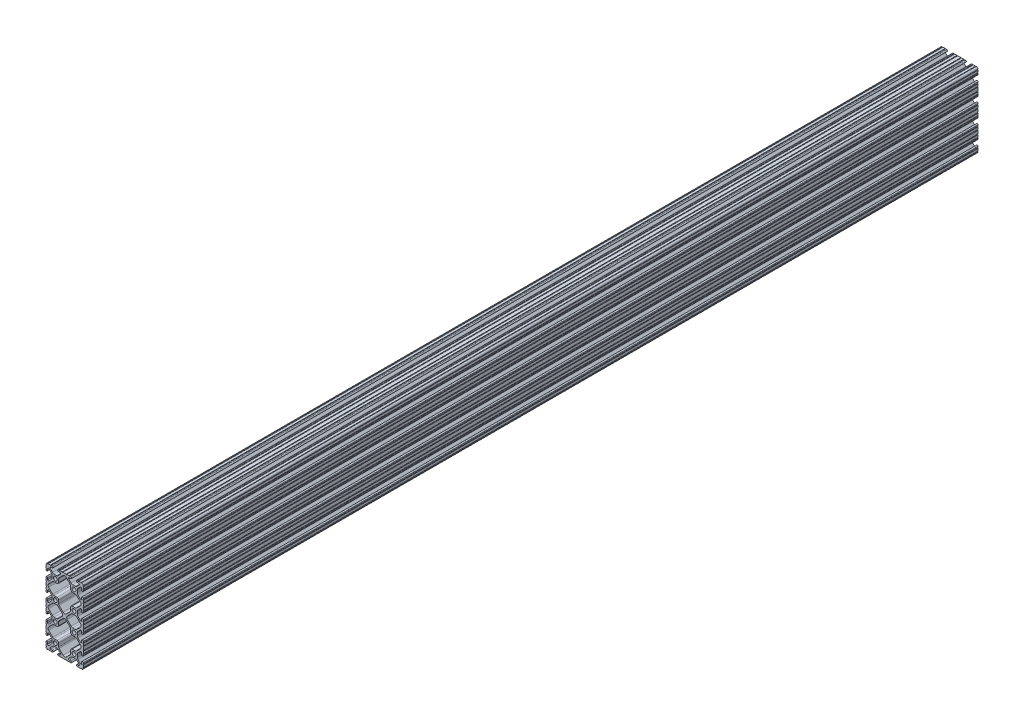
SolidWorks part; units mm, degrees
ref_plane "Front Plane" through (0, 0, 0) normal (0, 0, 1) x (1, 0, 0)
ref_plane "Top Plane" through (0, 0, 0) normal (0, 1, 0) x (1, 0, 0)
ref_plane "Right Plane" through (0, 0, 0) normal (1, 0, 0) x (0, 0, -1)
sketch "Sketch1" plane through (0, 0, 0) normal (0, 0, 1) x (1, 0, 0)
  line L0 (2.286, 55.2958) -> (-2.0184, 55.2958)
  line L1 (-3.5809, 55.943) -> (-9.0725, 61.4345)
  line L2 (-9.0725, 65.5655) -> (-3.5809, 71.057)
  line L3 (-2.0184, 71.7042) -> (2.286, 71.7042)
  line L4 (4.4958, 73.914) -> (4.4958, 78.2184)
  line L5 (5.143, 79.7809) -> (10.6345, 85.2725)
  line L6 (14.7655, 85.2725) -> (20.257, 79.7809)
  line L7 (20.9042, 78.2184) -> (20.9042, 73.914)
  line L8 (23.114, 71.7042) -> (27.4184, 71.7042)
  line L9 (28.9809, 71.057) -> (34.4725, 65.5655)
  line L10 (34.4725, 61.4345) -> (28.9809, 55.943)
  line L11 (27.4184, 55.2958) -> (23.114, 55.2958)
  line L12 (20.9042, 53.086) -> (20.9042, 48.7816)
  line L13 (20.257, 47.2191) -> (14.7655, 41.7275)
  line L14 (10.6345, 41.7275) -> (5.143, 47.2191)
  line L15 (4.4958, 48.7816) -> (4.4958, 53.086)
  line L16 (4.4958, 23.114) -> (4.4958, 27.4184)
  line L17 (5.143, 28.9809) -> (10.6345, 34.4725)
  line L18 (14.7655, 34.4725) -> (20.257, 28.9809)
  line L19 (20.9042, 27.4184) -> (20.9042, 23.114)
  line L20 (23.114, 20.9042) -> (27.4184, 20.9042)
  line L21 (28.9809, 20.257) -> (34.4725, 14.7655)
  line L22 (34.4725, 10.6345) -> (28.9809, 5.143)
  line L23 (27.4184, 4.4958) -> (23.114, 4.4958)
  line L24 (20.9042, 2.286) -> (20.9042, -2.0184)
  line L25 (20.257, -3.5809) -> (14.7655, -9.0725)
  line L26 (10.6345, -9.0725) -> (5.143, -3.5809)
  line L27 (4.4958, -2.0184) -> (4.4958, 2.286)
  line L28 (2.286, 4.4958) -> (-2.0184, 4.4958)
  line L29 (-3.5809, 5.143) -> (-9.0725, 10.6345)
  line L30 (-9.0725, 14.7655) -> (-3.5809, 20.257)
  line L31 (-2.0184, 20.9042) -> (2.286, 20.9042)
  line L32 (27.0186, 29.8958) -> (23.7824, 29.8958)
  line L33 (21.5373, 30.8258) -> (16.3286, 36.0346)
  line L34 (16.3286, 40.1654) -> (21.5373, 45.3742)
  line L35 (23.7824, 46.3042) -> (27.0186, 46.3042)
  line L36 (29.2636, 45.3743) -> (34.4725, 40.1655)
  line L37 (34.4725, 36.0345) -> (29.2636, 30.8257)
  line L38 (1.6176, 29.8958) -> (-1.6186, 29.8958)
  line L39 (-3.8636, 30.8257) -> (-9.0725, 36.0345)
  line L40 (-9.0725, 40.1655) -> (-3.8636, 45.3743)
  line L41 (-1.6186, 46.3042) -> (1.6176, 46.3042)
  line L42 (3.8627, 45.3742) -> (9.0714, 40.1654)
  line L43 (9.0714, 36.0346) -> (3.8627, 30.8258)
  line L44 (-12.7, 40.2336) -> (-12.7, 35.9664)
  line L45 (-12.7, 34.9504) -> (-12.7, 32.004)
  line L46 (-12.7, 30.988) -> (-12.7, 29.7434)
  line L47 (-10.4902, 29.7434) -> (-10.4902, 31.8743)
  line L48 (-8.7558, 32.5927) -> (-5.4258, 29.2627)
  line L49 (-4.4958, 27.0176) -> (-4.4958, 23.7824)
  line L50 (-5.4258, 21.5373) -> (-8.7558, 18.2073)
  line L51 (-10.4902, 18.9257) -> (-10.4902, 21.0566)
  line L52 (-12.7, 21.0566) -> (-12.7, 19.812)
  line L53 (-12.7, 18.796) -> (-12.7, 15.8496)
  line L54 (-12.7, 14.8336) -> (-12.7, 10.5664)
  line L55 (-12.7, 9.5504) -> (-12.7, 6.604)
  line L56 (-12.7, 5.588) -> (-12.7, 4.3434)
  line L57 (-10.4902, 4.3434) -> (-10.4902, 6.4743)
  line L58 (-8.7558, 7.1927) -> (-5.4258, 3.8627)
  line L59 (-4.4958, 1.6176) -> (-4.4958, -1.6176)
  line L60 (-5.4258, -3.8627) -> (-8.7558, -7.1927)
  line L61 (-10.4902, -6.4743) -> (-10.4902, -4.3434)
  line L62 (-12.7, -4.3434) -> (-12.7, -5.588)
  line L63 (-12.7, -6.604) -> (-12.7, -9.5504)
  line L64 (-9.5504, -12.7) -> (-6.604, -12.7)
  line L65 (-5.588, -12.7) -> (-4.3434, -12.7)
  line L66 (-4.3434, -10.4902) -> (-6.4743, -10.4902)
  line L67 (-7.1927, -8.7558) -> (-3.8627, -5.4258)
  line L68 (-1.6176, -4.4958) -> (1.6176, -4.4958)
  line L69 (3.8627, -5.4258) -> (7.1927, -8.7558)
  line L70 (6.4743, -10.4902) -> (4.3434, -10.4902)
  line L71 (4.3434, -12.7) -> (5.588, -12.7)
  line L72 (6.604, -12.7) -> (9.5504, -12.7)
  line L73 (10.5664, -12.7) -> (14.8336, -12.7)
  line L74 (15.8496, -12.7) -> (18.796, -12.7)
  line L75 (19.812, -12.7) -> (21.0566, -12.7)
  line L76 (21.0566, -10.4902) -> (18.9257, -10.4902)
  line L77 (18.2073, -8.7558) -> (21.5373, -5.4258)
  line L78 (23.7824, -4.4958) -> (27.0176, -4.4958)
  line L79 (29.2627, -5.4258) -> (32.5927, -8.7558)
  line L80 (31.8743, -10.4902) -> (29.7434, -10.4902)
  line L81 (29.7434, -12.7) -> (30.988, -12.7)
  line L82 (32.004, -12.7) -> (34.9504, -12.7)
  line L83 (38.1, -9.5504) -> (38.1, -6.604)
  line L84 (38.1, -5.588) -> (38.1, -4.3434)
  line L85 (35.8902, -4.3434) -> (35.8902, -6.4743)
  line L86 (34.1558, -7.1927) -> (30.8258, -3.8627)
  line L87 (29.8958, -1.6176) -> (29.8958, 1.6176)
  line L88 (30.8258, 3.8627) -> (34.1558, 7.1927)
  line L89 (35.8902, 6.4743) -> (35.8902, 4.3434)
  line L90 (38.1, 4.3434) -> (38.1, 5.588)
  line L91 (38.1, 6.604) -> (38.1, 9.5504)
  line L92 (38.1, 10.5664) -> (38.1, 14.8336)
  line L93 (38.1, 15.8496) -> (38.1, 18.796)
  line L94 (38.1, 19.812) -> (38.1, 21.0566)
  line L95 (35.8902, 21.0566) -> (35.8902, 18.9257)
  line L96 (34.1558, 18.2073) -> (30.8258, 21.5373)
  line L97 (29.8958, 23.7824) -> (29.8958, 27.0176)
  line L98 (30.8258, 29.2627) -> (34.1558, 32.5927)
  line L99 (35.8902, 31.8743) -> (35.8902, 29.7434)
  line L100 (38.1, 29.7434) -> (38.1, 30.988)
  line L101 (38.1, 32.004) -> (38.1, 34.9504)
  line L102 (38.1, 35.9664) -> (38.1, 40.2336)
  line L103 (38.1, 41.2496) -> (38.1, 44.196)
  line L104 (38.1, 45.212) -> (38.1, 46.4566)
  line L105 (35.8902, 46.4566) -> (35.8902, 44.3257)
  line L106 (34.1558, 43.6073) -> (30.8258, 46.9373)
  line L107 (29.8958, 49.1824) -> (29.8958, 52.4176)
  line L108 (30.8258, 54.6627) -> (34.1558, 57.9927)
  line L109 (35.8902, 57.2743) -> (35.8902, 55.1434)
  line L110 (38.1, 55.1434) -> (38.1, 56.388)
  line L111 (38.1, 57.404) -> (38.1, 60.3504)
  line L112 (38.1, 61.3664) -> (38.1, 65.6336)
  line L113 (38.1, 66.6496) -> (38.1, 69.596)
  line L114 (38.1, 70.612) -> (38.1, 71.8566)
  line L115 (35.8902, 71.8566) -> (35.8902, 69.7257)
  line L116 (34.1558, 69.0073) -> (30.8258, 72.3373)
  line L117 (29.8958, 74.5824) -> (29.8958, 77.8176)
  line L118 (30.8258, 80.0627) -> (34.1558, 83.3927)
  line L119 (35.8902, 82.6743) -> (35.8902, 80.5434)
  line L120 (38.1, 80.5434) -> (38.1, 81.788)
  line L121 (38.1, 82.804) -> (38.1, 85.7504)
  line L122 (34.9504, 88.9) -> (32.004, 88.9)
  line L123 (30.988, 88.9) -> (29.7434, 88.9)
  line L124 (29.7434, 86.6902) -> (31.8743, 86.6902)
  line L125 (32.5927, 84.9558) -> (29.2627, 81.6258)
  line L126 (27.0176, 80.6958) -> (23.7824, 80.6958)
  line L127 (21.5373, 81.6258) -> (18.2073, 84.9558)
  line L128 (18.9257, 86.6902) -> (21.0566, 86.6902)
  line L129 (21.0566, 88.9) -> (19.812, 88.9)
  line L130 (18.796, 88.9) -> (15.8496, 88.9)
  line L131 (14.8336, 88.9) -> (10.5664, 88.9)
  line L132 (9.5504, 88.9) -> (6.604, 88.9)
  line L133 (5.588, 88.9) -> (4.3434, 88.9)
  line L134 (4.3434, 86.6902) -> (6.4743, 86.6902)
  line L135 (7.1927, 84.9558) -> (3.8627, 81.6258)
  line L136 (1.6176, 80.6958) -> (-1.6176, 80.6958)
  line L137 (-3.8627, 81.6258) -> (-7.1927, 84.9558)
  line L138 (-6.4743, 86.6902) -> (-4.3434, 86.6902)
  line L139 (-4.3434, 88.9) -> (-5.588, 88.9)
  line L140 (-6.604, 88.9) -> (-9.5504, 88.9)
  line L141 (-12.7, 85.7504) -> (-12.7, 82.804)
  line L142 (-12.7, 81.788) -> (-12.7, 80.5434)
  line L143 (-10.4902, 80.5434) -> (-10.4902, 82.6743)
  line L144 (-8.7558, 83.3927) -> (-5.4258, 80.0627)
  line L145 (-4.4958, 77.8176) -> (-4.4958, 74.5824)
  line L146 (-5.4258, 72.3373) -> (-8.7558, 69.0073)
  line L147 (-10.4902, 69.7257) -> (-10.4902, 71.8566)
  line L148 (-12.7, 71.8566) -> (-12.7, 70.612)
  line L149 (-12.7, 69.596) -> (-12.7, 66.6496)
  line L150 (-12.7, 65.6336) -> (-12.7, 61.3664)
  line L151 (-12.7, 60.3504) -> (-12.7, 57.404)
  line L152 (-12.7, 56.388) -> (-12.7, 55.1434)
  line L153 (-10.4902, 55.1434) -> (-10.4902, 57.2743)
  line L154 (-8.7558, 57.9927) -> (-5.4258, 54.6627)
  line L155 (-4.4958, 52.4176) -> (-4.4958, 49.1824)
  line L156 (-5.4258, 46.9373) -> (-8.7558, 43.6073)
  line L157 (-10.4902, 44.3257) -> (-10.4902, 46.4566)
  line L158 (-12.7, 46.4566) -> (-12.7, 45.212)
  line L159 (-12.7, 44.196) -> (-12.7, 41.2496)
  arc A0 (4.4958, 53.086) -> (2.286, 55.2958) centre (2.286, 53.086) ccw
  arc A1 (-3.5809, 55.943) -> (-2.0184, 55.2958) centre (-2.0184, 57.5056) ccw
  arc A2 (-9.0725, 65.5655) -> (-9.0725, 61.4345) centre (-7.0071, 63.5) ccw
  arc A3 (-2.0184, 71.7042) -> (-3.5809, 71.057) centre (-2.0184, 69.4944) ccw
  arc A4 (2.286, 71.7042) -> (4.4958, 73.914) centre (2.286, 73.914) ccw
  arc A5 (5.143, 79.7809) -> (4.4958, 78.2184) centre (6.7056, 78.2184) ccw
  arc A6 (14.7655, 85.2725) -> (10.6345, 85.2725) centre (12.7, 83.2071) ccw
  arc A7 (20.9042, 78.2184) -> (20.257, 79.7809) centre (18.6944, 78.2184) ccw
  arc A8 (20.9042, 73.914) -> (23.114, 71.7042) centre (23.114, 73.914) ccw
  arc A9 (28.9809, 71.057) -> (27.4184, 71.7042) centre (27.4184, 69.4944) ccw
  arc A10 (34.4725, 61.4345) -> (34.4725, 65.5655) centre (32.4071, 63.5) ccw
  arc A11 (27.4184, 55.2958) -> (28.9809, 55.943) centre (27.4184, 57.5056) ccw
  arc A12 (23.114, 55.2958) -> (20.9042, 53.086) centre (23.114, 53.086) ccw
  arc A13 (20.257, 47.2191) -> (20.9042, 48.7816) centre (18.6944, 48.7816) ccw
  arc A14 (10.6345, 41.7275) -> (14.7655, 41.7275) centre (12.7, 43.7929) ccw
  arc A15 (4.4958, 48.7816) -> (5.143, 47.2191) centre (6.7056, 48.7816) ccw
  arc A16 (2.286, 20.9042) -> (4.4958, 23.114) centre (2.286, 23.114) ccw
  arc A17 (5.143, 28.9809) -> (4.4958, 27.4184) centre (6.7056, 27.4184) ccw
  arc A18 (14.7655, 34.4725) -> (10.6345, 34.4725) centre (12.7, 32.4071) ccw
  arc A19 (20.9042, 27.4184) -> (20.257, 28.9809) centre (18.6944, 27.4184) ccw
  arc A20 (20.9042, 23.114) -> (23.114, 20.9042) centre (23.114, 23.114) ccw
  arc A21 (28.9809, 20.257) -> (27.4184, 20.9042) centre (27.4184, 18.6944) ccw
  arc A22 (34.4725, 10.6345) -> (34.4725, 14.7655) centre (32.4071, 12.7) ccw
  arc A23 (27.4184, 4.4958) -> (28.9809, 5.143) centre (27.4184, 6.7056) ccw
  arc A24 (23.114, 4.4958) -> (20.9042, 2.286) centre (23.114, 2.286) ccw
  arc A25 (20.257, -3.5809) -> (20.9042, -2.0184) centre (18.6944, -2.0184) ccw
  arc A26 (10.6345, -9.0725) -> (14.7655, -9.0725) centre (12.7, -7.0071) ccw
  arc A27 (4.4958, -2.0184) -> (5.143, -3.5809) centre (6.7056, -2.0184) ccw
  arc A28 (4.4958, 2.286) -> (2.286, 4.4958) centre (2.286, 2.286) ccw
  arc A29 (-3.5809, 5.143) -> (-2.0184, 4.4958) centre (-2.0184, 6.7056) ccw
  arc A30 (-9.0725, 14.7655) -> (-9.0725, 10.6345) centre (-7.0071, 12.7) ccw
  arc A31 (-2.0184, 20.9042) -> (-3.5809, 20.257) centre (-2.0184, 18.6944) ccw
  arc A32 (27.0186, 29.8958) -> (29.2636, 30.8257) centre (27.0186, 33.0708) ccw
  arc A33 (21.5373, 30.8258) -> (23.7824, 29.8958) centre (23.7824, 33.0708) ccw
  arc A34 (16.3286, 40.1654) -> (16.3286, 36.0346) centre (18.3941, 38.1) ccw
  arc A35 (23.7824, 46.3042) -> (21.5373, 45.3742) centre (23.7824, 43.1292) ccw
  arc A36 (29.2636, 45.3743) -> (27.0186, 46.3042) centre (27.0186, 43.1292) ccw
  arc A37 (34.4725, 36.0345) -> (34.4725, 40.1655) centre (32.4071, 38.1) ccw
  arc A38 (1.6176, 29.8958) -> (3.8627, 30.8258) centre (1.6176, 33.0708) ccw
  arc A39 (-3.8636, 30.8257) -> (-1.6186, 29.8958) centre (-1.6186, 33.0708) ccw
  arc A40 (-9.0725, 40.1655) -> (-9.0725, 36.0345) centre (-7.0071, 38.1) ccw
  arc A41 (-1.6186, 46.3042) -> (-3.8636, 45.3743) centre (-1.6186, 43.1292) ccw
  arc A42 (3.8627, 45.3742) -> (1.6176, 46.3042) centre (1.6176, 43.1292) ccw
  arc A43 (9.0714, 36.0346) -> (9.0714, 40.1654) centre (7.0059, 38.1) ccw
  circle A44 centre (25.4, 76.2) radius 2.6035
  circle A45 centre (0, 76.2) radius 2.6035
  circle A46 centre (25.4, 50.8) radius 2.6035
  circle A47 centre (0, 50.8) radius 2.6035
  circle A48 centre (25.4, 0) radius 2.6035
  circle A49 centre (0, 0) radius 2.6035
  circle A50 centre (25.4, 25.4) radius 2.6035
  circle A51 centre (0, 25.4) radius 2.6035
  arc A52 (-12.7, 34.9504) -> (-12.7, 35.9664) centre (-12.7, 35.4584) ccw
  arc A53 (-12.7, 30.988) -> (-12.7, 32.004) centre (-12.7, 31.496) ccw
  arc A54 (-12.7, 29.7434) -> (-10.4902, 29.7434) centre (-11.5951, 29.7434) ccw
  arc A55 (-8.7558, 32.5927) -> (-10.4902, 31.8743) centre (-9.4742, 31.8743) ccw
  arc A56 (-4.4958, 27.0176) -> (-5.4258, 29.2627) centre (-7.6708, 27.0176) ccw
  arc A57 (-5.4258, 21.5373) -> (-4.4958, 23.7824) centre (-7.6708, 23.7824) ccw
  arc A58 (-10.4902, 18.9257) -> (-8.7558, 18.2073) centre (-9.4742, 18.9257) ccw
  arc A59 (-10.4902, 21.0566) -> (-12.7, 21.0566) centre (-11.5951, 21.0566) ccw
  arc A60 (-12.7, 18.796) -> (-12.7, 19.812) centre (-12.7, 19.304) ccw
  arc A61 (-12.7, 14.8336) -> (-12.7, 15.8496) centre (-12.7, 15.3416) ccw
  arc A62 (-12.7, 9.5504) -> (-12.7, 10.5664) centre (-12.7, 10.0584) ccw
  arc A63 (-12.7, 5.588) -> (-12.7, 6.604) centre (-12.7, 6.096) ccw
  arc A64 (-12.7, 4.3434) -> (-10.4902, 4.3434) centre (-11.5951, 4.3434) ccw
  arc A65 (-8.7558, 7.1927) -> (-10.4902, 6.4743) centre (-9.4742, 6.4743) ccw
  arc A66 (-4.4958, 1.6176) -> (-5.4258, 3.8627) centre (-7.6708, 1.6176) ccw
  arc A67 (-5.4258, -3.8627) -> (-4.4958, -1.6176) centre (-7.6708, -1.6176) ccw
  arc A68 (-10.4902, -6.4743) -> (-8.7558, -7.1927) centre (-9.4742, -6.4743) ccw
  arc A69 (-10.4902, -4.3434) -> (-12.7, -4.3434) centre (-11.5951, -4.3434) ccw
  arc A70 (-12.7, -6.604) -> (-12.7, -5.588) centre (-12.7, -6.096) ccw
  arc A71 (-12.6998, -10.5664) -> (-12.7, -9.5504) centre (-12.7, -10.0584) ccw
  arc A72 (-12.6998, -10.5664) -> (-10.5664, -12.6998) centre (-10.5918, -10.5918) ccw
  arc A73 (-9.5504, -12.7) -> (-10.5664, -12.6998) centre (-10.0584, -12.7) ccw
  arc A74 (-5.588, -12.7) -> (-6.604, -12.7) centre (-6.096, -12.7) ccw
  arc A75 (-4.3434, -12.7) -> (-4.3434, -10.4902) centre (-4.3434, -11.5951) ccw
  arc A76 (-7.1927, -8.7558) -> (-6.4743, -10.4902) centre (-6.4743, -9.4742) ccw
  arc A77 (-1.6176, -4.4958) -> (-3.8627, -5.4258) centre (-1.6176, -7.6708) ccw
  arc A78 (3.8627, -5.4258) -> (1.6176, -4.4958) centre (1.6176, -7.6708) ccw
  arc A79 (6.4743, -10.4902) -> (7.1927, -8.7558) centre (6.4743, -9.4742) ccw
  arc A80 (4.3434, -10.4902) -> (4.3434, -12.7) centre (4.3434, -11.5951) ccw
  arc A81 (6.604, -12.7) -> (5.588, -12.7) centre (6.096, -12.7) ccw
  arc A82 (10.5664, -12.7) -> (9.5504, -12.7) centre (10.0584, -12.7) ccw
  arc A83 (15.8496, -12.7) -> (14.8336, -12.7) centre (15.3416, -12.7) ccw
  arc A84 (19.812, -12.7) -> (18.796, -12.7) centre (19.304, -12.7) ccw
  arc A85 (21.0566, -12.7) -> (21.0566, -10.4902) centre (21.0566, -11.5951) ccw
  arc A86 (18.2073, -8.7558) -> (18.9257, -10.4902) centre (18.9257, -9.4742) ccw
  arc A87 (23.7824, -4.4958) -> (21.5373, -5.4258) centre (23.7824, -7.6708) ccw
  arc A88 (29.2627, -5.4258) -> (27.0176, -4.4958) centre (27.0176, -7.6708) ccw
  arc A89 (31.8743, -10.4902) -> (32.5927, -8.7558) centre (31.8743, -9.4742) ccw
  arc A90 (29.7434, -10.4902) -> (29.7434, -12.7) centre (29.7434, -11.5951) ccw
  arc A91 (32.004, -12.7) -> (30.988, -12.7) centre (31.496, -12.7) ccw
  arc A92 (35.9664, -12.6998) -> (34.9504, -12.7) centre (35.4584, -12.7) ccw
  arc A93 (35.9664, -12.6998) -> (38.0998, -10.5664) centre (35.9918, -10.5918) ccw
  arc A94 (38.1, -9.5504) -> (38.0998, -10.5664) centre (38.1, -10.0584) ccw
  arc A95 (38.1, -5.588) -> (38.1, -6.604) centre (38.1, -6.096) ccw
  arc A96 (38.1, -4.3434) -> (35.8902, -4.3434) centre (36.9951, -4.3434) ccw
  arc A97 (34.1558, -7.1927) -> (35.8902, -6.4743) centre (34.8742, -6.4743) ccw
  arc A98 (29.8958, -1.6176) -> (30.8258, -3.8627) centre (33.0708, -1.6176) ccw
  arc A99 (30.8258, 3.8627) -> (29.8958, 1.6176) centre (33.0708, 1.6176) ccw
  arc A100 (35.8902, 6.4743) -> (34.1558, 7.1927) centre (34.8742, 6.4743) ccw
  arc A101 (35.8902, 4.3434) -> (38.1, 4.3434) centre (36.9951, 4.3434) ccw
  arc A102 (38.1, 6.604) -> (38.1, 5.588) centre (38.1, 6.096) ccw
  arc A103 (38.1, 10.5664) -> (38.1, 9.5504) centre (38.1, 10.0584) ccw
  arc A104 (38.1, 15.8496) -> (38.1, 14.8336) centre (38.1, 15.3416) ccw
  arc A105 (38.1, 19.812) -> (38.1, 18.796) centre (38.1, 19.304) ccw
  arc A106 (38.1, 21.0566) -> (35.8902, 21.0566) centre (36.9951, 21.0566) ccw
  arc A107 (34.1558, 18.2073) -> (35.8902, 18.9257) centre (34.8742, 18.9257) ccw
  arc A108 (29.8958, 23.7824) -> (30.8258, 21.5373) centre (33.0708, 23.7824) ccw
  arc A109 (30.8258, 29.2627) -> (29.8958, 27.0176) centre (33.0708, 27.0176) ccw
  arc A110 (35.8902, 31.8743) -> (34.1558, 32.5927) centre (34.8742, 31.8743) ccw
  arc A111 (35.8902, 29.7434) -> (38.1, 29.7434) centre (36.9951, 29.7434) ccw
  arc A112 (38.1, 32.004) -> (38.1, 30.988) centre (38.1, 31.496) ccw
  arc A113 (38.1, 35.9664) -> (38.1, 34.9504) centre (38.1, 35.4584) ccw
  arc A114 (38.1, 41.2496) -> (38.1, 40.2336) centre (38.1, 40.7416) ccw
  arc A115 (38.1, 45.212) -> (38.1, 44.196) centre (38.1, 44.704) ccw
  arc A116 (38.1, 46.4566) -> (35.8902, 46.4566) centre (36.9951, 46.4566) ccw
  arc A117 (34.1558, 43.6073) -> (35.8902, 44.3257) centre (34.8742, 44.3257) ccw
  arc A118 (29.8958, 49.1824) -> (30.8258, 46.9373) centre (33.0708, 49.1824) ccw
  arc A119 (30.8258, 54.6627) -> (29.8958, 52.4176) centre (33.0708, 52.4176) ccw
  arc A120 (35.8902, 57.2743) -> (34.1558, 57.9927) centre (34.8742, 57.2743) ccw
  arc A121 (35.8902, 55.1434) -> (38.1, 55.1434) centre (36.9951, 55.1434) ccw
  arc A122 (38.1, 57.404) -> (38.1, 56.388) centre (38.1, 56.896) ccw
  arc A123 (38.1, 61.3664) -> (38.1, 60.3504) centre (38.1, 60.8584) ccw
  arc A124 (38.1, 66.6496) -> (38.1, 65.6336) centre (38.1, 66.1416) ccw
  arc A125 (38.1, 70.612) -> (38.1, 69.596) centre (38.1, 70.104) ccw
  arc A126 (38.1, 71.8566) -> (35.8902, 71.8566) centre (36.9951, 71.8566) ccw
  arc A127 (34.1558, 69.0073) -> (35.8902, 69.7257) centre (34.8742, 69.7257) ccw
  arc A128 (29.8958, 74.5824) -> (30.8258, 72.3373) centre (33.0708, 74.5824) ccw
  arc A129 (30.8258, 80.0627) -> (29.8958, 77.8176) centre (33.0708, 77.8176) ccw
  arc A130 (35.8902, 82.6743) -> (34.1558, 83.3927) centre (34.8742, 82.6743) ccw
  arc A131 (35.8902, 80.5434) -> (38.1, 80.5434) centre (36.9951, 80.5434) ccw
  arc A132 (38.1, 82.804) -> (38.1, 81.788) centre (38.1, 82.296) ccw
  arc A133 (38.0998, 86.7664) -> (38.1, 85.7504) centre (38.1, 86.2584) ccw
  arc A134 (38.0998, 86.7664) -> (35.9664, 88.8998) centre (35.9918, 86.7918) ccw
  arc A135 (34.9504, 88.9) -> (35.9664, 88.8998) centre (35.4584, 88.9) ccw
  arc A136 (30.988, 88.9) -> (32.004, 88.9) centre (31.496, 88.9) ccw
  arc A137 (29.7434, 88.9) -> (29.7434, 86.6902) centre (29.7434, 87.7951) ccw
  arc A138 (32.5927, 84.9558) -> (31.8743, 86.6902) centre (31.8743, 85.6742) ccw
  arc A139 (27.0176, 80.6958) -> (29.2627, 81.6258) centre (27.0176, 83.8708) ccw
  arc A140 (21.5373, 81.6258) -> (23.7824, 80.6958) centre (23.7824, 83.8708) ccw
  arc A141 (18.9257, 86.6902) -> (18.2073, 84.9558) centre (18.9257, 85.6742) ccw
  arc A142 (21.0566, 86.6902) -> (21.0566, 88.9) centre (21.0566, 87.7951) ccw
  arc A143 (18.796, 88.9) -> (19.812, 88.9) centre (19.304, 88.9) ccw
  arc A144 (14.8336, 88.9) -> (15.8496, 88.9) centre (15.3416, 88.9) ccw
  arc A145 (9.5504, 88.9) -> (10.5664, 88.9) centre (10.0584, 88.9) ccw
  arc A146 (5.588, 88.9) -> (6.604, 88.9) centre (6.096, 88.9) ccw
  arc A147 (4.3434, 88.9) -> (4.3434, 86.6902) centre (4.3434, 87.7951) ccw
  arc A148 (7.1927, 84.9558) -> (6.4743, 86.6902) centre (6.4743, 85.6742) ccw
  arc A149 (1.6176, 80.6958) -> (3.8627, 81.6258) centre (1.6176, 83.8708) ccw
  arc A150 (-3.8627, 81.6258) -> (-1.6176, 80.6958) centre (-1.6176, 83.8708) ccw
  arc A151 (-6.4743, 86.6902) -> (-7.1927, 84.9558) centre (-6.4743, 85.6742) ccw
  arc A152 (-4.3434, 86.6902) -> (-4.3434, 88.9) centre (-4.3434, 87.7951) ccw
  arc A153 (-6.604, 88.9) -> (-5.588, 88.9) centre (-6.096, 88.9) ccw
  arc A154 (-10.5664, 88.8998) -> (-9.5504, 88.9) centre (-10.0584, 88.9) ccw
  arc A155 (-10.5664, 88.8998) -> (-12.6998, 86.7664) centre (-10.5918, 86.7918) ccw
  arc A156 (-12.7, 85.7504) -> (-12.6998, 86.7664) centre (-12.7, 86.2584) ccw
  arc A157 (-12.7, 81.788) -> (-12.7, 82.804) centre (-12.7, 82.296) ccw
  arc A158 (-12.7, 80.5434) -> (-10.4902, 80.5434) centre (-11.5951, 80.5434) ccw
  arc A159 (-8.7558, 83.3927) -> (-10.4902, 82.6743) centre (-9.4742, 82.6743) ccw
  arc A160 (-4.4958, 77.8176) -> (-5.4258, 80.0627) centre (-7.6708, 77.8176) ccw
  arc A161 (-5.4258, 72.3373) -> (-4.4958, 74.5824) centre (-7.6708, 74.5824) ccw
  arc A162 (-10.4902, 69.7257) -> (-8.7558, 69.0073) centre (-9.4742, 69.7257) ccw
  arc A163 (-10.4902, 71.8566) -> (-12.7, 71.8566) centre (-11.5951, 71.8566) ccw
  arc A164 (-12.7, 69.596) -> (-12.7, 70.612) centre (-12.7, 70.104) ccw
  arc A165 (-12.7, 65.6336) -> (-12.7, 66.6496) centre (-12.7, 66.1416) ccw
  arc A166 (-12.7, 60.3504) -> (-12.7, 61.3664) centre (-12.7, 60.8584) ccw
  arc A167 (-12.7, 56.388) -> (-12.7, 57.404) centre (-12.7, 56.896) ccw
  arc A168 (-12.7, 55.1434) -> (-10.4902, 55.1434) centre (-11.5951, 55.1434) ccw
  arc A169 (-8.7558, 57.9927) -> (-10.4902, 57.2743) centre (-9.4742, 57.2743) ccw
  arc A170 (-4.4958, 52.4176) -> (-5.4258, 54.6627) centre (-7.6708, 52.4176) ccw
  arc A171 (-5.4258, 46.9373) -> (-4.4958, 49.1824) centre (-7.6708, 49.1824) ccw
  arc A172 (-10.4902, 44.3257) -> (-8.7558, 43.6073) centre (-9.4742, 44.3257) ccw
  arc A173 (-10.4902, 46.4566) -> (-12.7, 46.4566) centre (-11.5951, 46.4566) ccw
  arc A174 (-12.7, 44.196) -> (-12.7, 45.212) centre (-12.7, 44.704) ccw
  arc A175 (-12.7, 40.2336) -> (-12.7, 41.2496) centre (-12.7, 40.7416) ccw
extrude "Extrude1" add sketch "Sketch1" against normal blind 1219.2
